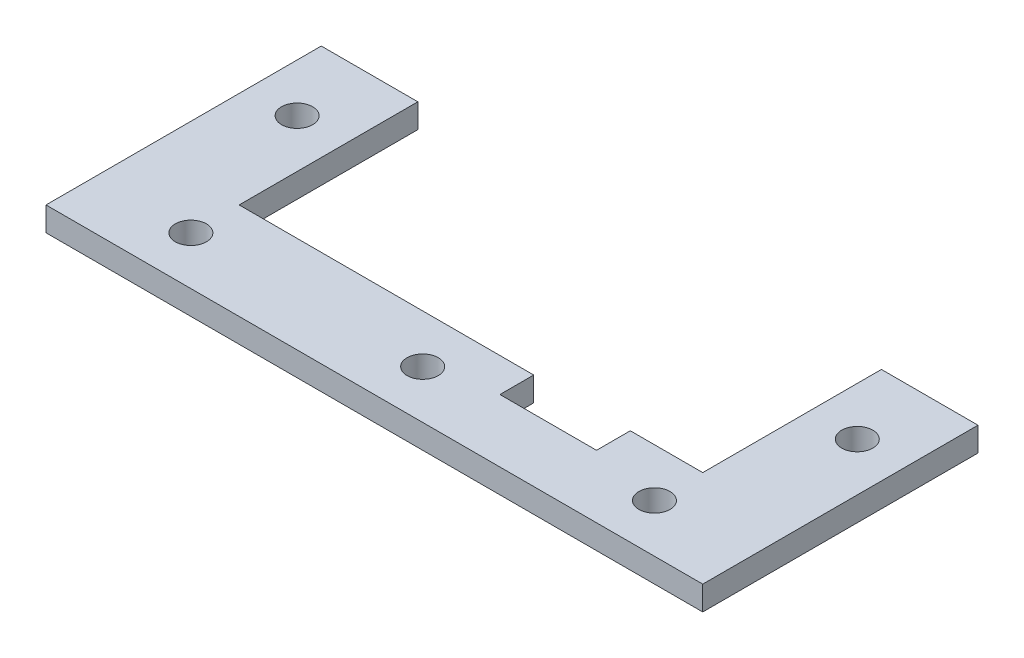
SolidWorks part; units mm, degrees
ref_plane "Front Plane" through (0, 0, 0) normal (0, 0, 1) x (1, 0, 0)
ref_plane "Top Plane" through (0, 0, 0) normal (0, 1, 0) x (1, 0, 0)
ref_plane "Right Plane" through (0, 0, 0) normal (1, 0, 0) x (0, 0, -1)
sketch "Sketch2" plane through (0, 0, 0) normal (0, 1, 0) x (1, 0, 0)
  line L0 (0, 0) -> (-20, 0)
  line L2 (0, 0) -> (0, -37)
  line L3 (0, -37) -> (96, -37)
  line L4 (96, 0) -> (96, -37)
  line L5 (-20, 0) -> (-20, -57)
  line L6 (-20, -57) -> (116, -57)
  line L7 (116, -57) -> (116, 0)
  line L8 (116, 0) -> (96, 0)
  dimension "D1" = 96
  dimension "D2" = 37
  dimension "D3" = 20
  dimension "D4" = 20
  dimension "D5" = 20
  dimension "D6" = 96
extrude "Boss-Extrude1" add sketch "Sketch2" along normal blind 5
sketch "Sketch3" plane through (0, 5, 0) normal (0, 1, 0) x (1, 0, 0)
  line L0 (96, -37) -> (0, -37) construction
  line L1 (81, -37) -> (61, -37)
  line L2 (81, -37) -> (81, -44)
  line L3 (81, -44) -> (61, -44)
  line L4 (61, -37) -> (61, -44)
  line L5 (96, 0) -> (96, -37) construction
  dimension "D1" = 15
  dimension "D2" = 35
  dimension "D3" = 7
extrude "Cut-Extrude1" cut sketch "Sketch3" against normal through all
sketch "Sketch4" plane through (0, 5, 0) normal (0, 1, 0) x (1, 0, 0)
  line L0 (0, -37) -> (0, 0) construction
  line L1 (0, 0) -> (-20, 0) construction
  line L2 (-20, -57) -> (116, -57) construction
  line L3 (-20, 0) -> (-20, -57) construction
  line L4 (96, 0) -> (96, -37) construction
  circle A0 centre (-10, -15) radius 3.225
  circle A1 centre (0, -47) radius 3.225
  circle A2 centre (48, -47) radius 3.225
  circle A3 centre (96, -47) radius 3.225
  circle A4 centre (106, -15) radius 3.225
  point P10 (0, 0)
  point P11 (0, 0)
  point P12 (0, 0)
  point P14 (0, 0)
  dimension "D2" = 6.45
  dimension "D3" = 6.45
  dimension "D4" = 6.45
  dimension "D5" = 6.45
  dimension "D6" = 6.45
  dimension "D1" = 48
  dimension "D7" = 15
  dimension "D8" = 10
  dimension "D9" = 10
  dimension "D10" = 10
extrude "Cut-Extrude2" cut sketch "Sketch4" against normal through all
